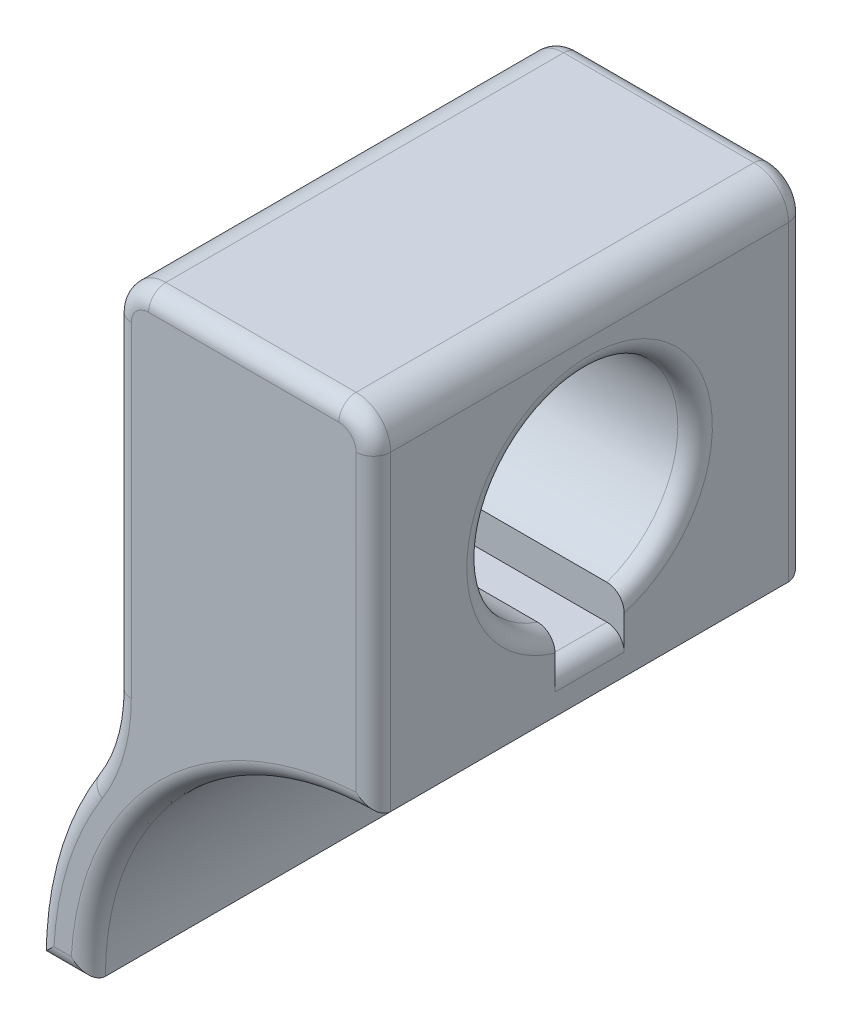
SolidWorks part; units mm, degrees
ref_plane "Front Plane" through (0, 0, 0) normal (0, 0, 1) x (1, 0, 0)
ref_plane "Top Plane" through (0, 0, 0) normal (0, 1, 0) x (1, 0, 0)
ref_plane "Right Plane" through (0, 0, 0) normal (1, 0, 0) x (0, 0, -1)
sketch "Sketch1" plane through (0, 0, 0) normal (0, 0, 1) x (1, 0, 0)
  line L0 (0, 13.7615) -> (0, -27.1597) construction
  line L1 (-27.0234, 0) -> (31.0656, 0) construction
  line L2 (-19.5, 0) -> (-16.5, 0)
  line L4 (0, 16.5) -> (0, 34.5)
  line L5 (-2, 36.5) -> (-13, 36.5)
  line L6 (-15, 34.5) -> (-15, 15.6605)
  arc A0 (0, 16.5) -> (-16.5, 0) centre (0, 0) ccw
  arc A1 (-16.5254, 10.3518) -> (-19.5, 0) centre (0, 0) ccw
  circle A2 centre (0, 0) radius 19.5 construction
  circle A3 centre (0, 0) radius 16.5 construction
  arc A4 (-15, 15.6605) -> (-16.5254, 10.3518) centre (-25, 15.6605) cw
  arc A5 (0, 34.5) -> (-2, 36.5) centre (-2, 34.5) ccw
  arc A6 (-13, 36.5) -> (-15, 34.5) centre (-13, 34.5) ccw
  point P21 (0, 36.5)
  point P24 (-15, 36.5)
  dimension "D1" = 33
  dimension "D4" = 10
  dimension "D5" = 2
  dimension "D3" = 15
  dimension "D6" = 20
  dimension "D2" = 3
extrude "Boss-Extrude1" add sketch "Sketch1" along normal blind 25
sketch "Sketch2" plane through (0, 0, 0) normal (1, 0, 0) x (0, 0, -1)
  line L0 (-12.5, 34.5) -> (-12.5, 16.5) construction
  line L1 (-25, 34.5) -> (0, 34.5) construction
  line L2 (-25, 16.5) -> (0, 16.5) construction
  line L3 (-25, 36.5) -> (0, 36.5) construction
  line L4 (-14.5, 18.7372) -> (-10.5, 18.7372)
  line L5 (-10.5, 18.7372) -> (-10.5, 20.7372)
  line L6 (-14.5, 18.7372) -> (-14.5, 20.7372)
  arc A0 (-10.5, 20.7372) -> (-14.5, 20.7372) centre (-12.5, 26.5) ccw
  dimension "D1" = 12.2
  dimension "D2" = 10
  dimension "D3" = 2
  dimension "D4" = 2
  dimension "D5" = 2
extrude "Cut-Extrude1" cut sketch "Sketch2" against normal through all
fillet "Fillet1" radius 1 2 edges at (-15, 18.7372, 12.5) (0, 18.7372, 12.5)
fillet "Fillet2" radius 1 2 edges at (-15, 32.6, 12.5) (0, 32.6, 12.5)
fillet "Fillet3" radius 1 18 edges at (-18, 0, 0) (-11.6673, 11.6673, 0) (0, 25.5, 0) (-0.5858, 35.9142, 0) (-7.5, 36.5, 0) (-14.4142, 35.9142, 0) (-15, 25.0802, 0) (-15.3889, 12.8987, 0) (-18.7416, 5.3854, 0) (-15.3889, 12.8987, 25) (-15, 25.0802, 25) (-14.4142, 35.9142, 25) (-7.5, 36.5, 25) (-0.5858, 35.9142, 25) (0, 25.5, 25) (-11.6673, 11.6673, 25) (-18, 0, 25) (-18.7416, 5.3854, 25)
